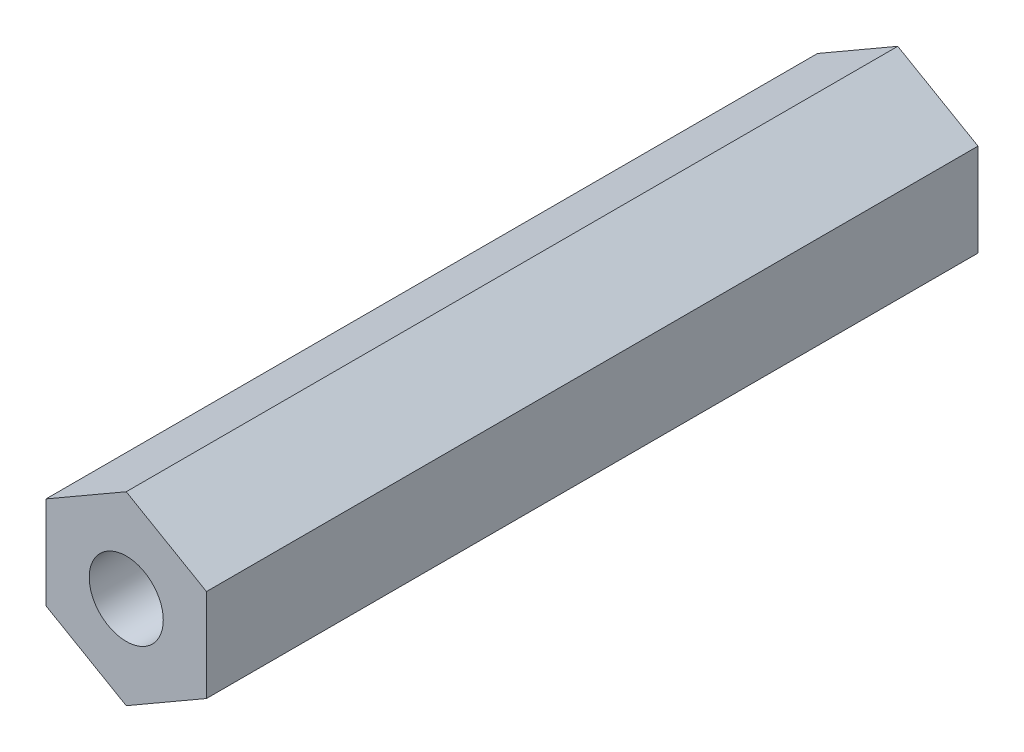
SolidWorks part; units mm, degrees
material "黄铜"
ref_plane "前视基准面" through (0, 0, 0) normal (0, 0, 1) x (1, 0, 0)
ref_plane "上视基准面" through (0, 0, 0) normal (0, 1, 0) x (1, 0, 0)
ref_plane "右视基准面" through (0, 0, 0) normal (1, 0, 0) x (0, 0, -1)
sketch "草图1" plane through (0, 0, 0) normal (0, 0, 1) x (1, 0, 0)
  line L1 (-2.6, 1.5011) -> (-2.6, -1.5011)
  line L2 (-2.6, -1.5011) -> (0, -3.0022)
  line L3 (0, -3.0022) -> (2.6, -1.5011)
  line L4 (2.6, -1.5011) -> (2.6, 1.5011)
  line L5 (2.6, 1.5011) -> (0, 3.0022)
  line L6 (0, 3.0022) -> (-2.6, 1.5011)
  circle A0 centre (0, 0) radius 2.6 construction
  circle A1 centre (0, 0) radius 1.2
  dimension "D2" = 2.4
  dimension "D1" = 5.2
extrude "凸台-拉伸1" add sketch "草图1" along normal blind 25
